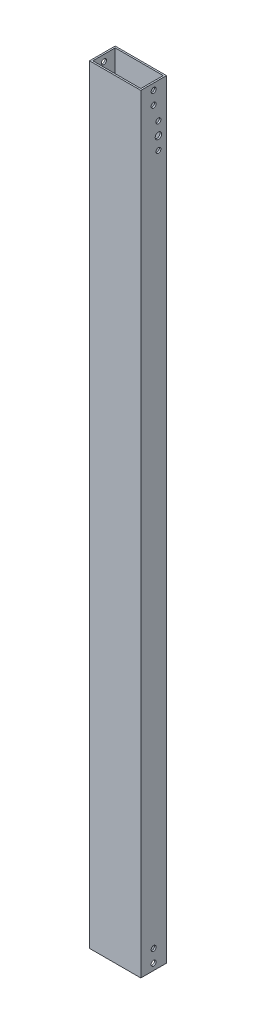
SolidWorks part; units mm, degrees
ref_plane "Front Plane" through (0, 0, 0) normal (0, 0, 1) x (1, 0, 0)
ref_plane "Top Plane" through (0, 0, 0) normal (0, 1, 0) x (1, 0, 0)
ref_plane "Right Plane" through (0, 0, 0) normal (1, 0, 0) x (0, 0, -1)
sketch "Sketch1" plane through (0, 0, 0) normal (0, 0, 1) x (1, 0, 0)
  line L1 (-25.4, -381) -> (25.4, -381)
  line L2 (-25.4, -381) -> (-25.4, 381)
  line L3 (-25.4, 381) -> (25.4, 381)
  line L4 (25.4, -381) -> (25.4, 381)
  line L5 (-25.4, -381) -> (25.4, 381) construction
  line L6 (-25.4, 381) -> (25.4, -381) construction
  point P0 (0, 0)
  dimension "D1" = 50.8
  dimension "D2" = 762
extrude "Boss-Extrude1" add sketch "Sketch1" along normal mid plane 25.4
shell "Shell1" thickness 1.5875
sketch "Sketch3" plane through (0, 0, 0) normal (1, 0, 0) x (0, 0, -1)
  line L0 (-12.7, -381) -> (12.7, -381) construction
  circle A0 centre (0, -374.65) radius 2.4892
  circle A1 centre (0, -361.95) radius 2.4892
  point P6 (0, -381)
  dimension "D1" = 4.9784
  dimension "D2" = 6.35
  dimension "D3" = 12.7
extrude "Cut-Extrude1" cut sketch "Sketch3" against normal through all both and the other way through all
sketch "Sketch4" plane through (0, 0, 0) normal (1, 0, 0) x (0, 0, -1)
  line L0 (12.7, 381) -> (12.7, -381) construction
  line L3 (-12.7, 381) -> (12.7, 381) construction
  circle A0 centre (4.7625, 333.375) radius 3.175
  circle A1 centre (4.7625, 346.075) radius 2.4892
  circle A2 centre (4.7625, 320.675) radius 2.4892
  dimension "D1" = 6.35
  dimension "D4" = 4.9784
  dimension "D2" = 7.9375
  dimension "D5" = 12.7
  dimension "D6" = 12.7
  dimension "D3" = 47.625
extrude "Cut-Extrude2" cut sketch "Sketch4" against normal through all both and the other way through all
mirror "Mirror1" about plane through (0, 0, 0) normal (0, 1, 0) of "Cut-Extrude1"
equation "\"D6@Sketch4\"=\"D5@Sketch4\""
